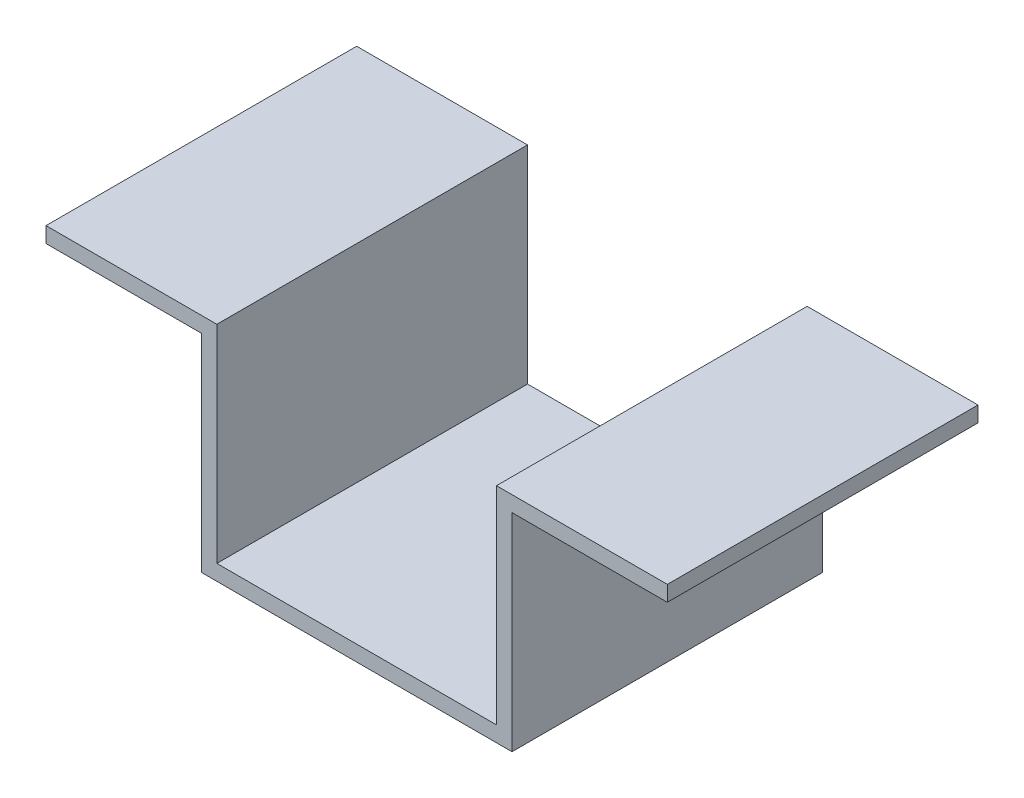
SolidWorks part; units mm, degrees
ref_plane "前视基准面" through (0, 0, 0) normal (0, 0, 1) x (1, 0, 0)
ref_plane "上视基准面" through (0, 0, 0) normal (0, 1, 0) x (1, 0, 0)
ref_plane "右视基准面" through (0, 0, 0) normal (1, 0, 0) x (0, 0, -1)
sketch "草图1" plane through (0, 0, 0) normal (0, 0, 1) x (1, 0, 0)
  line L0 (0, 0) -> (34.94, 0) construction
  line L1 (0, 0) -> (0, 19.2061) construction
  line L2 (-30, 10) -> (-15, 10)
  line L3 (-15, 10) -> (-15, -10)
  line L4 (-15, -10) -> (0, -10)
  line L5 (-30, 11.5) -> (-13.5, 11.5)
  line L6 (-13.5, 11.5) -> (-13.5, -8.5)
  line L7 (-13.5, -8.5) -> (0, -8.5)
  line L8 (-30, 11.5) -> (-30, 10)
  line L9 (30, 11.5) -> (30, 10)
  line L10 (15, -10) -> (0, -10)
  line L11 (13.5, -8.5) -> (0, -8.5)
  line L12 (15, 10) -> (15, -10)
  line L13 (13.5, 11.5) -> (13.5, -8.5)
  line L14 (30, 10) -> (15, 10)
  line L15 (30, 11.5) -> (13.5, 11.5)
  dimension "D1" = 10
  dimension "D2" = 15
  dimension "D3" = 30
  dimension "D4" = 10
  dimension "D5" = 1.5
extrude "凸台-拉伸1" add sketch "草图1" along normal blind 30
